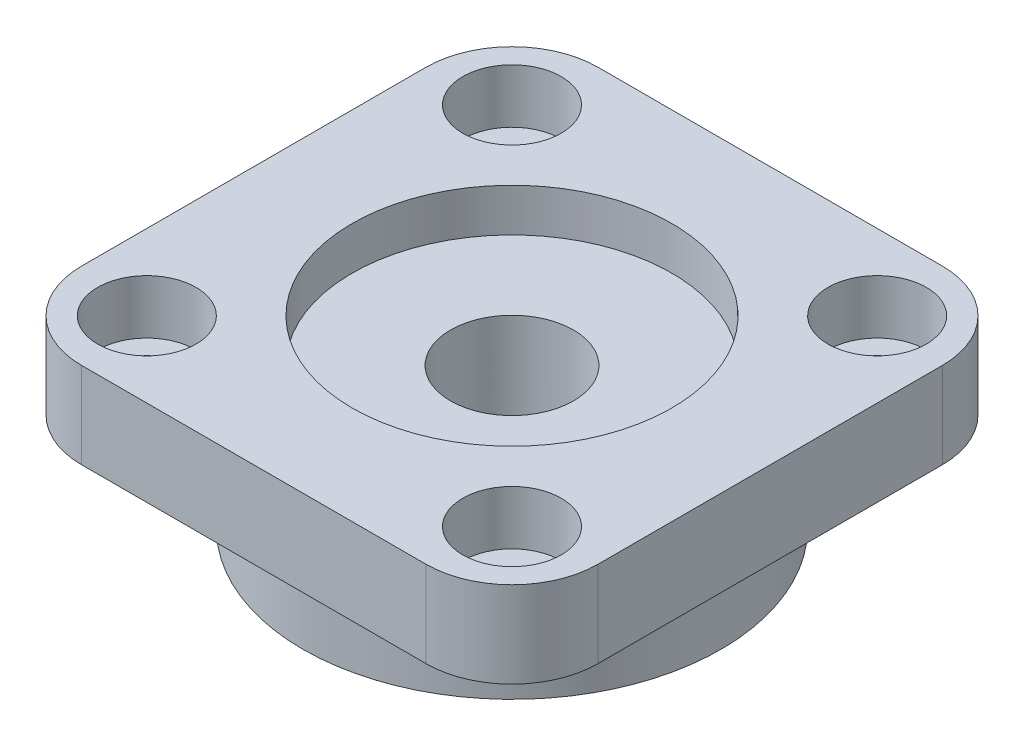
SolidWorks part; units mm, degrees
ref_plane "Front Plane" through (0, 0, 0) normal (0, 0, 1) x (1, 0, 0)
ref_plane "Top Plane" through (0, 0, 0) normal (0, 1, 0) x (1, 0, 0)
ref_plane "Right Plane" through (0, 0, 0) normal (1, 0, 0) x (0, 0, -1)
sketch "Sketch1" plane through (0, 0, 0) normal (0, 1, 0) x (1, 0, 0)
  circle A0 centre (0, 0) radius 17
  circle A1 centre (0, 0) radius 5
  dimension "D1" = 34
  dimension "D2" = 10
extrude "Boss-Extrude1" add sketch "Sketch1" along normal blind 8
sketch "Sketch2" plane through (0, 8, 0) normal (0, 1, 0) x (1, 0, 0)
  line L1 (21, -21) -> (-21, -21)
  line L2 (21, -21) -> (21, 21)
  line L3 (21, 21) -> (-21, 21)
  line L4 (-21, -21) -> (-21, 21)
  line L5 (21, -21) -> (-21, 21) construction
  line L6 (21, 21) -> (-21, -21) construction
  circle A0 centre (0, 0) radius 5
  point P0 (0, 0)
  dimension "D1" = 42
extrude "Boss-Extrude2" add sketch "Sketch2" along normal blind 7
fillet "Fillet1" radius 7 4 edges at (-21, 11.5, 21) (21, 11.5, 21) (21, 11.5, -21) (-21, 11.5, -21)
sketch "Sketch3" plane through (0, 15, 0) normal (0, 1, 0) x (1, 0, 0)
  line L0 (0, 0) -> (21, 0) construction
  line L1 (21, -14) -> (21, 14) construction
  line L2 (0, 0) -> (0, 21) construction
  line L3 (14, 21) -> (-14, 21) construction
  line L4 (0, 0) -> (22.7556, 22.7556) construction
  point P5 (14.8492, 14.8492)
  point P17 (14.8492, -14.8492)
  point P18 (-14.8492, -14.8492)
  point P19 (-14.8492, 14.8492)
  point P20 (0, 0)
  dimension "D2" = 4
  dimension "D1" = 21
hole_wizard "CBORE for M4 Hex Socket Head Cap Screw1" positions "3DSketch1" profile "Sketch4" counterbore size "M4" standard "ISO" end condition through all
sketch3d "3DSketch1"
  point P0 (-14.8492, 15, -14.8492)
  point P3 (14.8492, 15, -14.8492)
  point P6 (14.8492, 15, 14.8492)
  point P9 (-14.8492, 15, 14.8492)
sketch "Sketch4" plane through (-14.8492, 15, -14.8492) normal (1, 0, 0) x (0, 0, 1)
  line L0 (0, 0) -> (0, 15)
  line L1 (0, 15) -> (2.25, 15)
  line L3 (2.25, 15) -> (2.25, 4.4)
  line L4 (2.25, 4.4) -> (4, 4.4)
  line L5 (4, 4.4) -> (4, 0)
  line L7 (4, 0) -> (0, 0)
  line L11 (0, -6.35) -> (0, 107.95) construction
  dimension "Thru Hole Dia." = 4.5
  dimension "Thru Hole Depth" = 15
  dimension "C'Bore Dia." = 8
  dimension "C'Bore Depth" = 4.4
sketch "Sketch5" plane through (0, 0, 0) normal (0, -1, 0) x (1, 0, 0)
  circle A0 centre (0, 0) radius 13
  dimension "D1" = 26
extrude "Cut-Extrude1" cut sketch "Sketch5" against normal blind 3.5
sketch "Sketch6" plane through (0, 15, 0) normal (0, 1, 0) x (1, 0, 0)
  circle A0 centre (0, 0) radius 13
  dimension "D1" = 26
extrude "Cut-Extrude2" cut sketch "Sketch6" against normal blind 3.5
